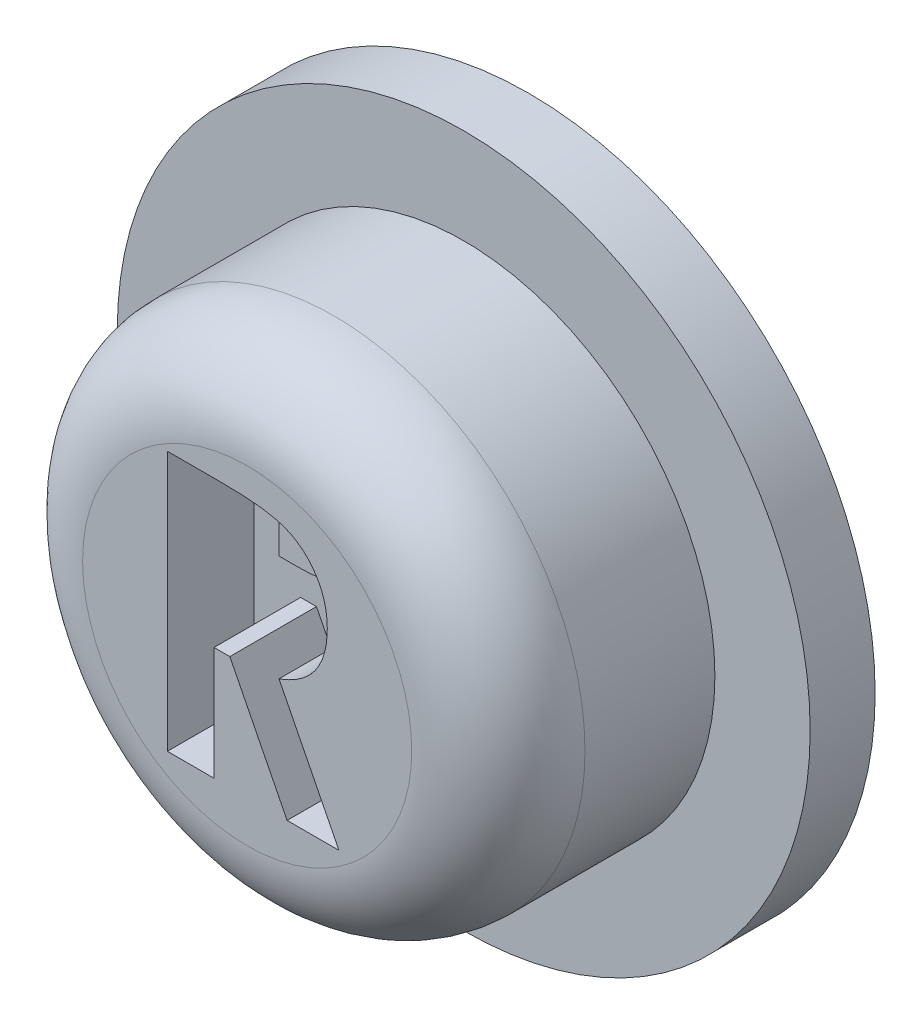
SolidWorks part; units mm, degrees
material "ABS"
ref_plane "Płaszczyzna przednia" through (0, 0, 0) normal (0, 0, 1) x (1, 0, 0)
ref_plane "Płaszczyzna górna" through (0, 0, 0) normal (0, 1, 0) x (1, 0, 0)
ref_plane "Płaszczyzna prawa" through (0, 0, 0) normal (1, 0, 0) x (0, 0, -1)
sketch "Szkic1" plane through (0, 0, 0) normal (0, 0, 1) x (1, 0, 0)
  circle A0 centre (0, 0) radius 4
  dimension "D1" = 8
extrude "Dodanie-wyciągnięcie1" add sketch "Szkic1" along normal blind 0.75
sketch "Szkic2" plane through (0, 0, 0.75) normal (0, 0, 1) x (1, 0, 0)
  circle A0 centre (0, 0) radius 2.9
  dimension "D1" = 5.8
extrude "Dodanie-wyciągnięcie2" add sketch "Szkic2" along normal blind 2.5
sketch "Szkic3" plane through (0, 0, 0) normal (0, 0, -1) x (-1, 0, 0)
  line L1 (-1.25, 1.25) -> (1.25, 1.25)
  line L2 (-1.25, 1.25) -> (-1.25, -1.25)
  line L3 (-1.25, -1.25) -> (1.25, -1.25)
  line L4 (1.25, 1.25) -> (1.25, -1.25)
  line L5 (-1.25, 1.25) -> (1.25, -1.25) construction
  line L6 (-1.25, -1.25) -> (1.25, 1.25) construction
  point P0 (0, 0)
  dimension "D1" = 2.5
extrude "Wytnij-wyciągnięcie1" cut sketch "Szkic3" against normal blind 1
fillet "Zaokrąglenie1" [suppressed] radius 1
fillet "Zaokrąglenie2" radius 1 1 edges at (2.9, 0, 3.25)
sketch "Szkic4" plane through (0, 0, 0) normal (0, 0, -1) x (-1, 0, 0)
  line L8 (1.45, 1.45) -> (-1.45, 1.45)
  line L9 (-1.45, 1.45) -> (-1.45, -1.45)
  line L10 (-1.45, -1.45) -> (1.45, -1.45)
  line L11 (1.45, -1.45) -> (1.45, 1.45)
  line L12 (1.45, 1.45) -> (-1.45, 1.45)
  line L13 (-1.45, 1.45) -> (-1.45, -1.45)
  line L14 (-1.45, -1.45) -> (1.45, -1.45)
  line L15 (1.45, -1.45) -> (1.45, 1.45)
  dimension "D1" = 0.2
extrude "Wytnij-wyciągnięcie2" cut sketch "Szkic4" against normal up to surface (1 mm away) up to face at (0, 0, 1)
sketch "Szkic5" plane through (0, 0, 3.25) normal (0, 0, 1) x (1, 0, 0)
  circle A0 centre (0, 0) radius 1.9 construction
  text T0 "<b><r>R</r></b>" font "Century Gothic" height 3
extrude "Wytnij-wyciągnięcie3" cut sketch "Szkic5" against normal blind 1
sketch "Szkic6" plane through (0, 0, 3.25) normal (0, 0, 1) x (1, 0, 0)
  line L3 (-0.1994, 1.046) -> (-0.3827, 1.046)
  line L4 (-0.3827, 1.046) -> (-0.3827, 0.4306)
  line L5 (-0.3827, 0.4306) -> (-0.173, 0.4306)
  line L6 (-0.1994, 1.046) -> (-0.3827, 1.046)
  line L7 (-0.3827, 1.046) -> (-0.3827, 0.4306)
  line L8 (-0.3827, 0.4306) -> (-0.173, 0.4306)
  spline S2 degree 3 poles (1.8301, -1999.5343) (-9.5335, 11.356) (-4.7464, 0.2626) (-0.0276, 0.434) (0.0365, 0.4402) (0.0944, 0.448) (0.1464, 0.457) (0.1921, 0.4699) (0.232, 0.4838) (0.2659, 0.501) (0.2948, 0.5205) (0.3197, 0.5428) (0.3403, 0.5685) (0.3573, 0.597) (0.3705, 0.6286) (0.3802, 0.6629) (0.6429, 2.4846) (-14.4486, 5.2591) (1996.6734, -119.2637) knots -19.135267 -19.135267 -19.135267 -19.135267 0.10554 0.202086 0.290685 0.370553 0.44267 0.507675 0.565573 0.616455 0.663331 0.708862 0.753412 0.798515 0.845064 0.893873 0.944708 8.396967 8.396967 8.396967 8.396967 only from (-0.173, 0.4306) to (0.3865, 0.7395)
  spline S3 degree 3 poles (1985.5, 243.9767) (-18.6051, -4.9366) (0.8098, -0.8189) (0.3728, 0.8316) (0.3538, 0.8732) (0.3279, 0.9113) (0.2952, 0.9446) (0.2576, 0.9741) (0.2144, 0.9973) (0.1745, 1.0127) (0.1381, 1.0219) (0.1053, 1.0287) (0.0672, 1.0336) (0.024, 1.0387) (-0.0243, 1.042) (-0.078, 1.0445) (-5.909, 1.1431) (-11.726, -6.2905) (-16.4982, 2000.893) knots -6.620855 -6.620855 -6.620855 -6.620855 0.063769 0.125262 0.185414 0.246807 0.309422 0.372533 0.437733 0.50575 0.544013 0.58837 0.640389 0.697897 0.763272 0.834979 0.913874 24.193276 24.193276 24.193276 24.193276 only from (0.3865, 0.7395) to (-0.1994, 1.046)
  spline S4 degree 3 poles (-0.173, 0.4306) (-0.1473, 0.4309) (-0.0982, 0.4314) (-0.0276, 0.434) (0.0365, 0.4402) (0.0944, 0.448) (0.1464, 0.457) (0.1921, 0.4699) (0.232, 0.4838) (0.2659, 0.501) (0.2948, 0.5205) (0.3197, 0.5428) (0.3403, 0.5685) (0.3573, 0.597) (0.3705, 0.6286) (0.3802, 0.6629) (0.3856, 0.7002) (0.3862, 0.726) (0.3865, 0.7395) knots 0 0 0 0 0.10554 0.202086 0.290685 0.370553 0.44267 0.507675 0.565573 0.616455 0.663331 0.708862 0.753412 0.798515 0.845064 0.893873 0.944708 1 1 1 1
  spline S5 degree 3 poles (0.3865, 0.7395) (0.3859, 0.7554) (0.3847, 0.7866) (0.3728, 0.8316) (0.3538, 0.8732) (0.3279, 0.9113) (0.2952, 0.9446) (0.2576, 0.9741) (0.2144, 0.9973) (0.1745, 1.0127) (0.1381, 1.0219) (0.1053, 1.0287) (0.0672, 1.0336) (0.024, 1.0387) (-0.0243, 1.042) (-0.078, 1.0445) (-0.1369, 1.0455) (-0.178, 1.0458) (-0.1994, 1.046) knots 0 0 0 0 0.063769 0.125262 0.185414 0.246807 0.309422 0.372533 0.437733 0.50575 0.544013 0.58837 0.640389 0.697897 0.763272 0.834979 0.913874 1 1 1 1
  dimension "D1" = 0
extrude "Wytnij-wyciągnięcie4" cut sketch "Szkic6" against normal blind 0.75
